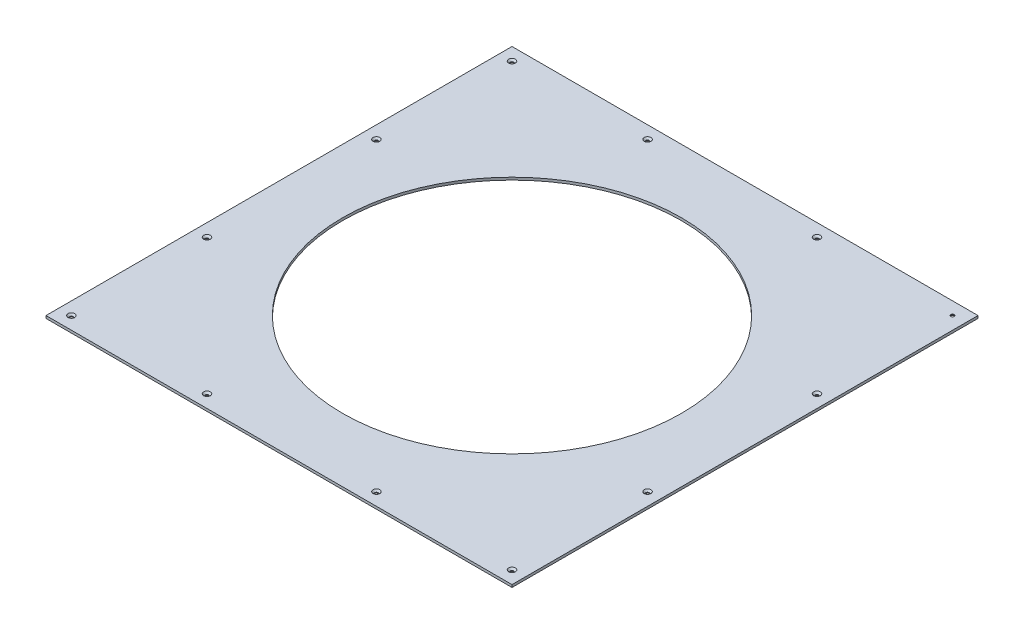
SolidWorks part; units mm, degrees
material "1060 合金"
ref_plane "前视基准面" through (0, 0, 0) normal (0, 0, 1) x (1, 0, 0)
ref_plane "上视基准面" through (0, 0, 0) normal (0, 1, 0) x (1, 0, 0)
ref_plane "右视基准面" through (0, 0, 0) normal (1, 0, 0) x (0, 0, -1)
sketch "草图1" plane through (0, 0, 0) normal (0, 1, 0) x (1, 0, 0)
  line L1 (-275, 275) -> (275, 275)
  line L2 (-275, 275) -> (-275, -275)
  line L3 (-275, -275) -> (275, -275)
  line L4 (275, 275) -> (275, -275)
  circle A0 centre (0, 0) radius 200
  point P4 (0, 275)
  point P6 (275, 0)
  dimension "D3" = 400
  dimension "D1" = 550
  dimension "D2" = 550
extrude "凸台-拉伸1" add sketch "草图1" along normal blind 3
sketch "草图2" plane through (0, 0, 0) normal (0, 1, 0) x (1, 0, 0)
  line L0 (0, 0) -> (0, 275) construction
  line L1 (275, 275) -> (-275, 275) construction
  line L2 (-275, 275) -> (-275, -275) construction
  line L3 (275, -275) -> (275, 275) construction
  line L4 (-275, -275) -> (275, -275) construction
  circle A0 centre (-260, 260) radius 2
  circle A1 centre (-100, 260) radius 2
  circle A2 centre (100, 260) radius 2
  circle A4 centre (260, -100) radius 2
  circle A5 centre (260, 100) radius 2
  circle A6 centre (260, 260) radius 2
  circle A7 centre (-100, -260) radius 2
  circle A8 centre (100, -260) radius 2
  circle A9 centre (260, -260) radius 2
  circle A10 centre (-260, 100) radius 2
  circle A11 centre (-260, -100) radius 2
  circle A12 centre (-260, -260) radius 2
  dimension "D1" = 4
  dimension "D2" = 15
  dimension "D3" = 15
  dimension "D4" = 100
  dimension "D6" = 15
  dimension "D7" = 15
  dimension "D5" = 4
extrude "切除-拉伸1" cut sketch "草图2" along normal through all
chamfer "倒角1" distance 2 angle 45 12 edges at (-100, 3, -258) (-260, 3, -258) (-260, 3, -102) (-260, 3, 102) (-260, 3, 262) (-100, 3, 258) (100, 3, 262) (260, 3, 262) (260, 3, 98) (260, 3, -98) (260, 0, -258) (100, 3, -262)
